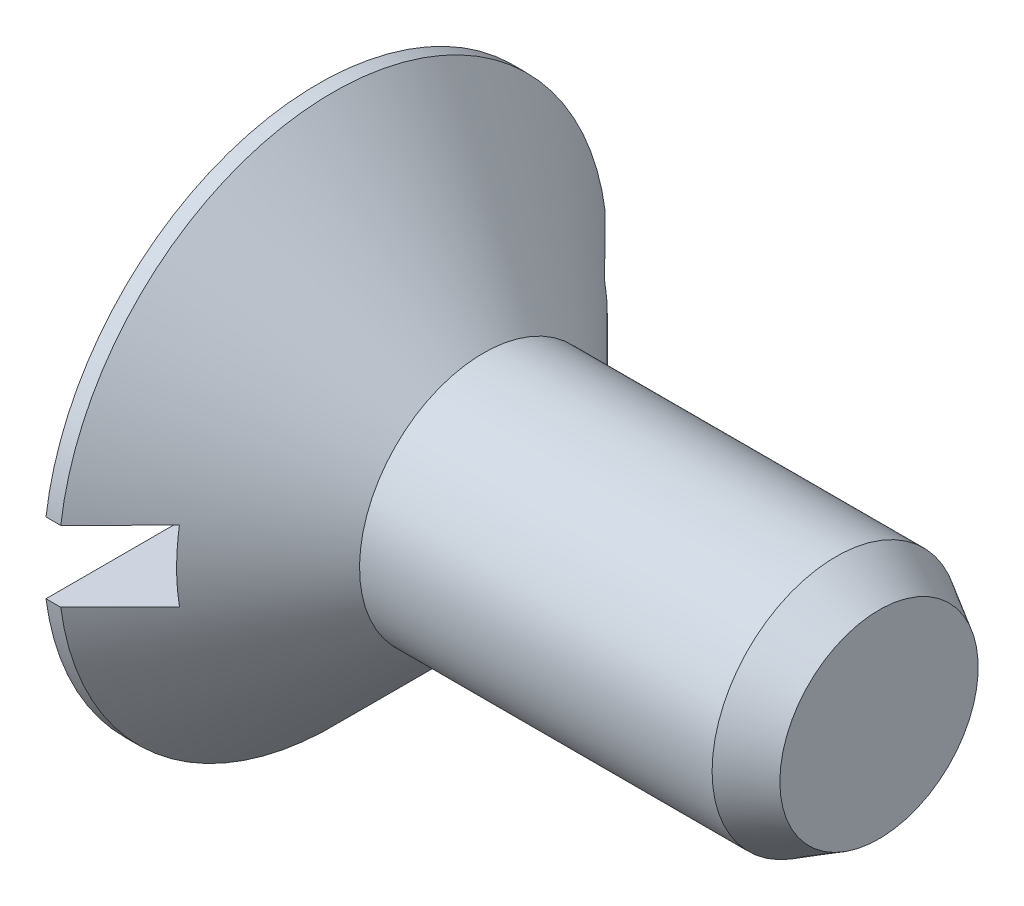
SolidWorks part; units mm, degrees
ref_plane "Front" through (0, 0, 0) normal (0, 0, 1) x (1, 0, 0)
ref_plane "Top" through (0, 0, 0) normal (0, 1, 0) x (1, 0, 0)
ref_plane "Right" through (0, 0, 0) normal (1, 0, 0) x (0, 0, -1)
sketch "Sketch1" plane through (0, 0, 0) normal (0, 0, 1) x (1, 0, 0)
  line L0 (0, 4.65) -> (0.25, 4.65)
  line L1 (0.25, 4.65) -> (2.8, 2.1)
  line L2 (2.8, 2.1) -> (9.5, 2.1)
  line L3 (9.5, 2.1) -> (9.5, 0)
  line L4 (9.5, 0) -> (0, 0)
  line L5 (0, 0) -> (0, 4.65)
  line L6 (6.6207, 0) -> (-0.9387, 0) construction
  dimension "D1" = 45
  dimension "d" = 4.2
  dimension "dK" = 9.3
  dimension "l" = 9.5
  dimension "k" = 2.8
revolve "Revolve1" add sketch "Sketch1" angle 360 about L6
cosmetic thread "ThreadCosmetic" [suppressed] parameters "D2"=3.8
sketch "Sketch2" plane through (0, 0, 0) normal (0, 0, 1) x (1, 0, 0)
  line L0 (0, 4.65) -> (0, -4.65) construction
  line L1 (0, 0.6) -> (1.25, 0.6)
  line L2 (0, 0.6) -> (0, -0.6)
  line L3 (0, -0.6) -> (1.25, -0.6)
  line L4 (1.25, 0.6) -> (1.25, -0.6)
  dimension "n" = 1.2
  dimension "t" = 1.25
extrude "Cut-Extrude1" cut sketch "Sketch2" against normal through all and the other way through all
chamfer "Chamfer1" distance 0.42 angle 60 1 edges at (9.5, 0, -2.1)
sketch "Sketch4" plane through (0, 0, 0) normal (0, 0, 1) x (1, 0, 0)
  line L0 (3.2136, 1.9) -> (2.9636, 1.9)
  line L1 (2.9636, 1.9) -> (2.8481, 2.1)
  line L2 (3.2136, 1.9) -> (3.329, 2.1)
  line L3 (2.8481, 2.1) -> (2.8481, 2.35)
  line L4 (3.329, 2.1) -> (3.329, 2.35)
  line L5 (2.8481, 2.35) -> (3.329, 2.35)
  line L6 (3.0886, 1.9) -> (3.0886, 0) construction
  line L7 (0, 0) -> (7.3035, 0) construction
  line L9 (8.7725, 2.1) -> (2.8, 2.1) construction
  line L12 (2.8, 2.1) -> (2.8, -2.1) construction
  dimension "D2" = 60
  dimension "D3" = 0.25
  dimension "advance" = 0.4809
  dimension "minordia" = 3.8
  dimension "threadstart" = 0.2886
revolve "ThreadSchematic" [suppressed] cut sketch "Sketch4" angle 360 about L7
pattern_linear "ThdSchPat" [suppressed] count 14 spacing 0.4809 along (-1, 0, 0)
sketch "Sketch3" plane through (0, 0, 0) normal (0, 0, 1) x (1, 0, 0)
  line L0 (2.8, 2.1) -> (9.5, 2.1) construction
  line L2 (7.5, 2.1) -> (8, 2.1) construction
  line L3 (9.5, 2.1) -> (9.5, 0) construction
  line L4 (8, 2.1) -> (9.5, 0)
  line L5 (2.9, 0) -> (5.4301, 0) construction
  line L6 (9.5, 0) -> (9.7, 0)
  line L7 (9.7, 0) -> (9.7, 2.1)
  line L8 (9.7, 2.1) -> (9.5, 2.1)
  line L9 (8, 2.1) -> (9.5, 2.1)
  dimension "y" = 2
  dimension "D1" = 0.5
revolve "EndCone" [suppressed] cut sketch "Sketch3" angle 360 about L5
equation "\"minordia@Sketch4\" = \"D2@ThreadCosmetic\""
equation "\"D1@Chamfer1\" = \"d@Sketch1\" / 10"
equation "\"D1@Sketch3\" = \"y@Sketch3\" / 4"
equation "\"threadstart@Sketch4\" = \"advance@Sketch4\"*0.6"
equation "\"D1@ThdSchPat\" = int(((\"l@Sketch1\"-\"k@Sketch1\")/\"advance@Sketch4\") + 0.999)"
equation "\"D3@ThdSchPat\" =\"advance@Sketch4\""
